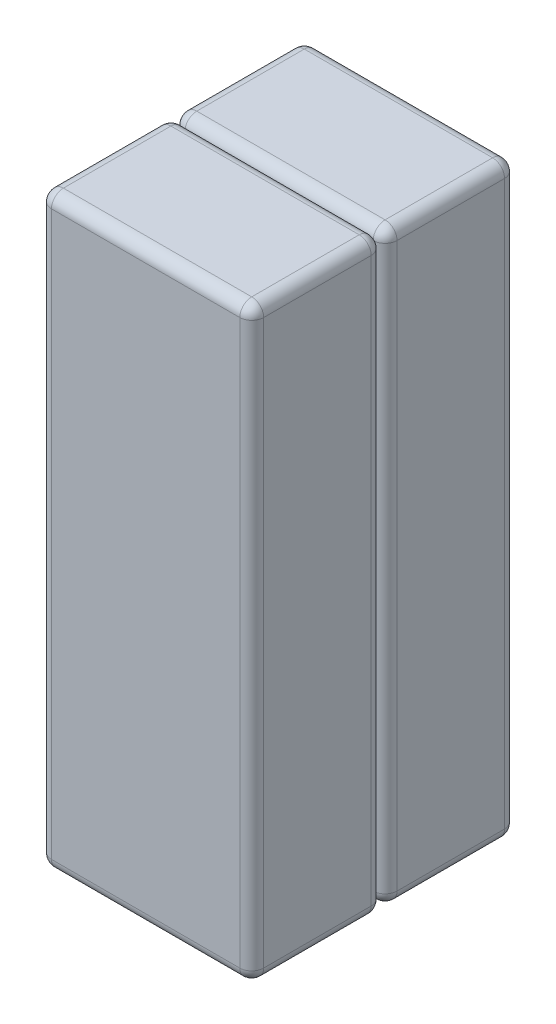
SolidWorks part; units mm, degrees
ref_plane "Front Plane" through (0, 0, 0) normal (0, 0, 1) x (1, 0, 0)
ref_plane "Top Plane" through (0, 0, 0) normal (0, 1, 0) x (1, 0, 0)
ref_plane "Right Plane" through (0, 0, 0) normal (1, 0, 0) x (0, 0, -1)
sketch "Sketch1" plane through (0, 0, 0) normal (0, 0, 1) x (1, 0, 0)
  line L0 (-43.3013, 135) -> (-26.65, 135) construction
  line L1 (-26.65, 205.5428) -> (26.65, 205.5428)
  line L2 (-26.65, 205.5428) -> (-26.65, 58.0428)
  line L3 (-26.65, 58.0428) -> (26.65, 58.0428)
  line L4 (26.65, 205.5428) -> (26.65, 58.0428)
  line L5 (-43.3013, 140) -> (-43.3013, 130) construction
  line L6 (43.3013, 135) -> (26.65, 135) construction
  line L7 (43.3013, 140) -> (43.3013, 130) construction
  dimension "D1" = 53.3
  dimension "D2" = 147.5
extrude "Boss-Extrude1" add sketch "Sketch1" along normal blind 33
fillet "Fillet2" radius 3 12 edges at (-26.65, 131.7928, 33) (-26.65, 131.7928, 0) (26.65, 131.7928, 33) (26.65, 131.7928, 0) (-26.65, 58.0428, 16.5) (0, 58.0428, 33) (26.65, 58.0428, 16.5) (0, 58.0428, 0) (26.65, 205.5428, 16.5) (0, 205.5428, 33) (-26.65, 205.5428, 16.5) (0, 205.5428, 0)
pattern_linear "LPattern3" count 2 spacing 33.5 along (0, 0, -1) of bodies 101
